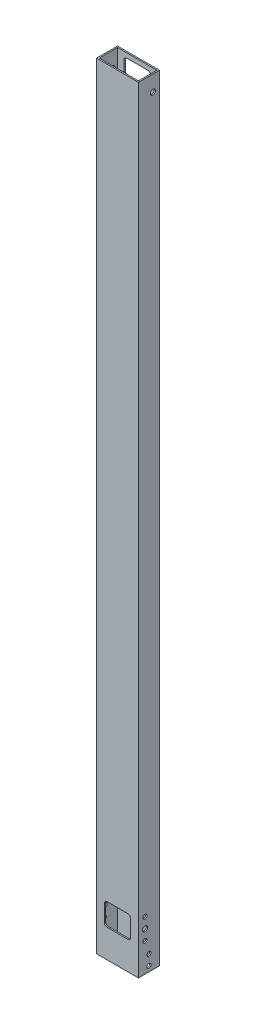
SolidWorks part; units mm, degrees
material "6061-T6 (SS)"
ref_plane "Front Plane" through (0, 0, 0) normal (0, 0, 1) x (1, 0, 0)
ref_plane "Top Plane" through (0, 0, 0) normal (0, 1, 0) x (1, 0, 0)
ref_plane "Right Plane" through (0, 0, 0) normal (1, 0, 0) x (0, 0, -1)
sketch "Sketch1" plane through (0, 0, 0) normal (0, 0, 1) x (1, 0, 0)
  line L1 (-25.4, -469.9) -> (25.4, -469.9)
  line L2 (-25.4, -469.9) -> (-25.4, 469.9)
  line L3 (-25.4, 469.9) -> (25.4, 469.9)
  line L4 (25.4, -469.9) -> (25.4, 469.9)
  line L5 (-25.4, -469.9) -> (25.4, 469.9) construction
  line L6 (-25.4, 469.9) -> (25.4, -469.9) construction
  point P0 (0, 0)
  dimension "D1" = 50.8
  dimension "D2" = 939.8
extrude "Boss-Extrude1" add sketch "Sketch1" along normal mid plane 25.4
shell "Shell1" thickness 1.5875
sketch "Sketch3" plane through (0, 0, 0) normal (1, 0, 0) x (0, 0, -1)
  line L0 (-12.7, -469.9) -> (12.7, -469.9) construction
  circle A0 centre (0, -463.55) radius 2.4892
  circle A1 centre (0, -450.85) radius 2.4892
  point P6 (0, -469.9)
  dimension "D1" = 4.9784
  dimension "D2" = 6.35
  dimension "D3" = 12.7
extrude "Cut-Extrude1" cut sketch "Sketch3" against normal through all both and the other way through all
sketch "Sketch4" plane through (0, 0, 0) normal (1, 0, 0) x (0, 0, -1)
  line L4 (-12.7, -469.9) -> (12.7, -469.9) construction
  line L5 (-12.7, 469.9) -> (-12.7, -469.9) construction
  circle A3 centre (-4.7625, -422.275) radius 3.175
  circle A4 centre (-4.7625, -409.575) radius 2.4892
  circle A5 centre (-4.7625, -434.975) radius 2.4892
  dimension "D7" = 6.35
  dimension "D8" = 4.9784
  dimension "D9" = 12.7
  dimension "D10" = 12.7
  dimension "D11" = 47.625
  dimension "D12" = 7.9375
extrude "Cut-Extrude2" cut sketch "Sketch4" against normal through all both and the other way through all
sketch "Sketch5" plane through (0, 0, 0) normal (0, 0, 1) x (1, 0, 0)
  line L0 (-25.4, -469.9) -> (25.4, -469.9) construction
  line L1 (-15.875, -408.7812) -> (15.875, -408.7812)
  line L2 (-15.875, -408.7812) -> (-15.875, -435.7687)
  line L3 (-15.875, -435.7687) -> (15.875, -435.7687)
  line L4 (15.875, -408.7812) -> (15.875, -435.7687)
  point P4 (0, -435.7687)
  point P7 (0, -469.9)
  point P8 (15.875, -422.275)
  dimension "D1" = 31.75
  dimension "D2" = 26.9875
  dimension "D3" = 47.625
extrude "Cut-Extrude3" cut sketch "Sketch5" along normal through all
fillet "Fillet1" radius 3.175 4 edges at (-15.875, -435.7687, 11.9062) (15.875, -435.7687, 11.9062) (-15.875, -408.7812, 11.9062) (15.875, -408.7812, 11.9062)
sketch "Sketch6" plane through (0, 0, 0) normal (1, 0, 0) x (0, 0, -1)
  line L0 (12.7, 469.9) -> (12.7, -469.9) construction
  line L1 (-12.7, 469.9) -> (12.7, 469.9) construction
  circle A0 centre (4.7625, 450.85) radius 3.175
  dimension "D1" = 6.35
  dimension "D2" = 7.9375
  dimension "D3" = 19.05
extrude "Cut-Extrude4" cut sketch "Sketch6" against normal through all both and the other way through all
sketch "Sketch7" plane through (0, 0, 0) normal (0, 0, 1) x (1, 0, 0)
  line L0 (25.4, 469.9) -> (-25.4, 469.9) construction
  line L1 (15.875, 464.3438) -> (-15.875, 464.3437)
  line L2 (15.875, 464.3438) -> (15.875, 437.3562)
  line L3 (15.875, 437.3562) -> (-15.875, 437.3562)
  line L4 (-15.875, 464.3437) -> (-15.875, 437.3562)
  point P5 (0, 464.3437)
  point P8 (0, 469.9)
  point P9 (-15.875, 450.85)
  dimension "D1" = 26.9875
  dimension "D2" = 31.75
  dimension "D3" = 19.05
extrude "Cut-Extrude5" cut sketch "Sketch7" against normal through all
fillet "Fillet2" radius 3.175 4 edges at (15.875, 437.3562, -11.9062) (-15.875, 437.3562, -11.9062) (-15.875, 464.3437, -11.9062) (15.875, 464.3438, -11.9062)
